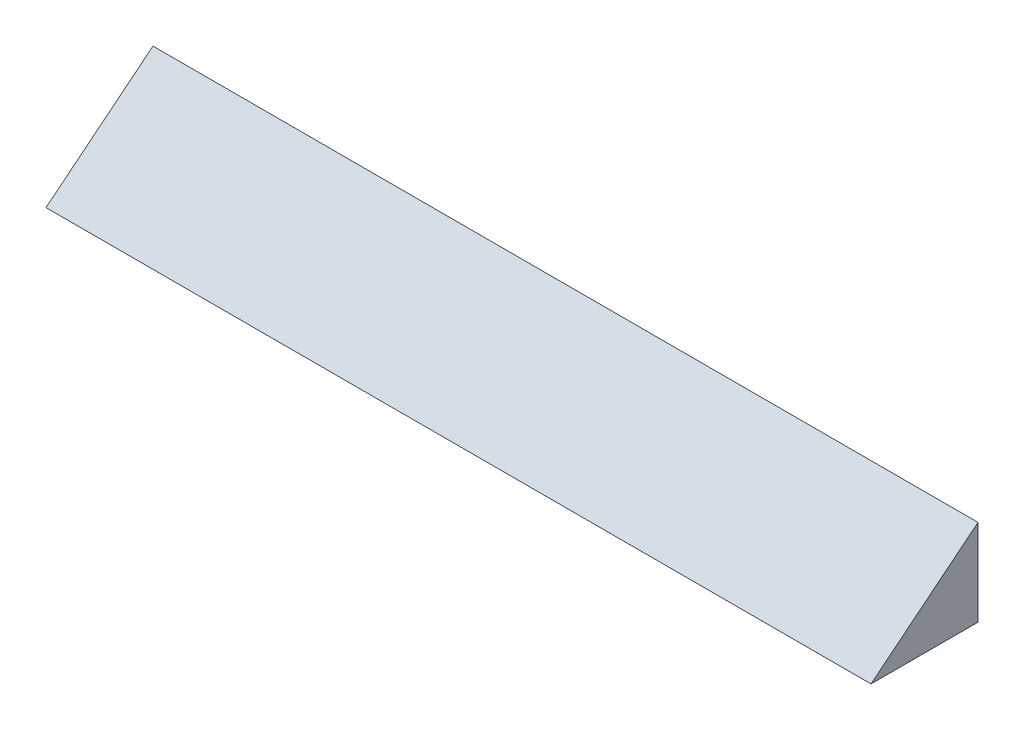
SolidWorks part; units mm, degrees
ref_plane "Front Plane" through (0, 0, 0) normal (0, 0, 1) x (1, 0, 0)
ref_plane "Top Plane" through (0, 0, 0) normal (0, 1, 0) x (1, 0, 0)
ref_plane "Right Plane" through (0, 0, 0) normal (1, 0, 0) x (0, 0, -1)
sketch "Sketch1" plane through (0, 0, 0) normal (1, 0, 0) x (0, 0, -1)
  line L0 (-44.6966, 5.8379) -> (73.8617, 101.5965)
  line L1 (-44.6966, 5.8379) -> (73.8617, 5.8379)
  line L2 (73.8617, 5.8379) -> (73.8617, 101.5965)
extrude "Boss-Extrude1" add sketch "Sketch1" along normal blind 914.4 contours L2 L0 L1
